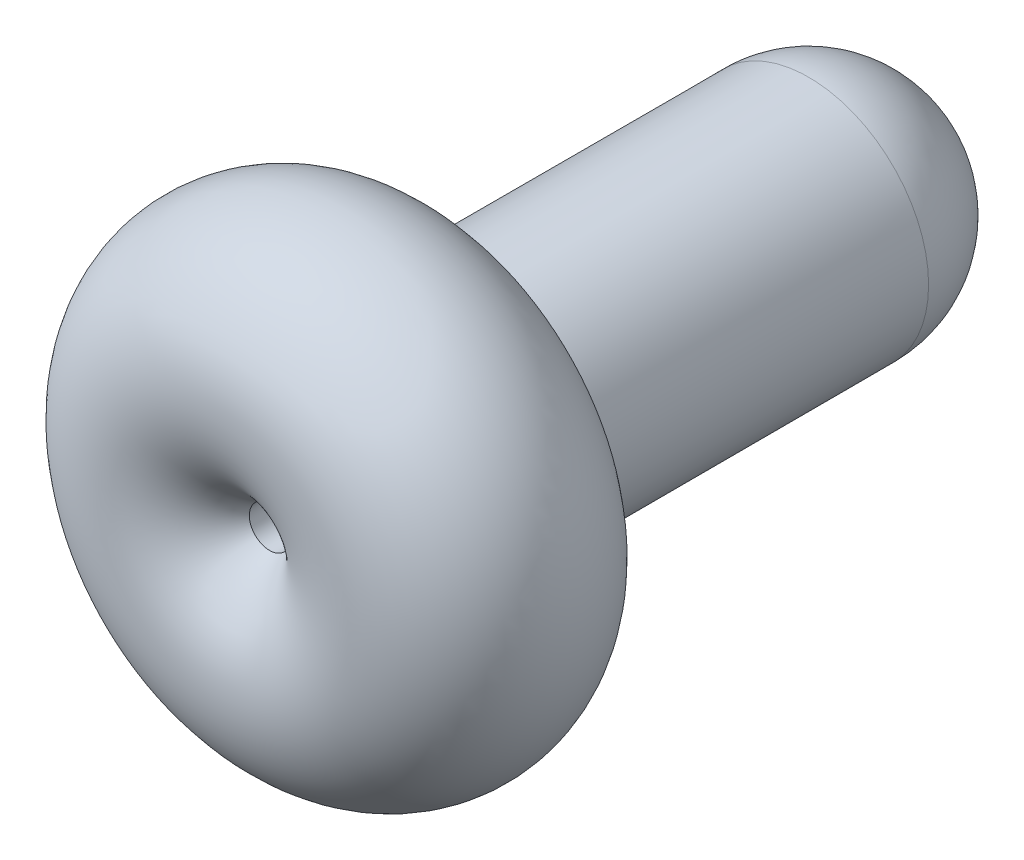
SolidWorks part; units mm, degrees
ref_plane "Front Plane" through (0, 0, 0) normal (0, 0, 1) x (1, 0, 0)
ref_plane "Top Plane" through (0, 0, 0) normal (0, 1, 0) x (1, 0, 0)
ref_plane "Right Plane" through (0, 0, 0) normal (1, 0, 0) x (0, 0, -1)
sketch "Sketch1" plane through (0, 0, 0) normal (0, 1, 0) x (1, 0, 0)
  line L0 (-29.7296, 29.7296) -> (-29.7296, 116.7296)
  line L4 (0, 0) -> (-0.1244, 146.3349) construction
  line L5 (-0.1244, 146.3349) -> (0, 0)
  arc A0 (-29.7296, 29.7296) -> (0, 0) centre (-29.7296, 0) ccw
  arc A2 (-29.7296, 116.7296) -> (-0.1244, 146.3349) centre (-0.1244, 116.7296) cw
revolve "Revolve1" add sketch "Sketch1" angle 360 about L4
sketch "Sketch2" plane through (0, 0, 0) normal (0, 0, 1) x (1, 0, 0)
  circle A0 centre (0, 0) radius 5
  dimension "D1" = 10
extrude "Cut-Extrude1" cut sketch "Sketch2" along normal mid plane 100
